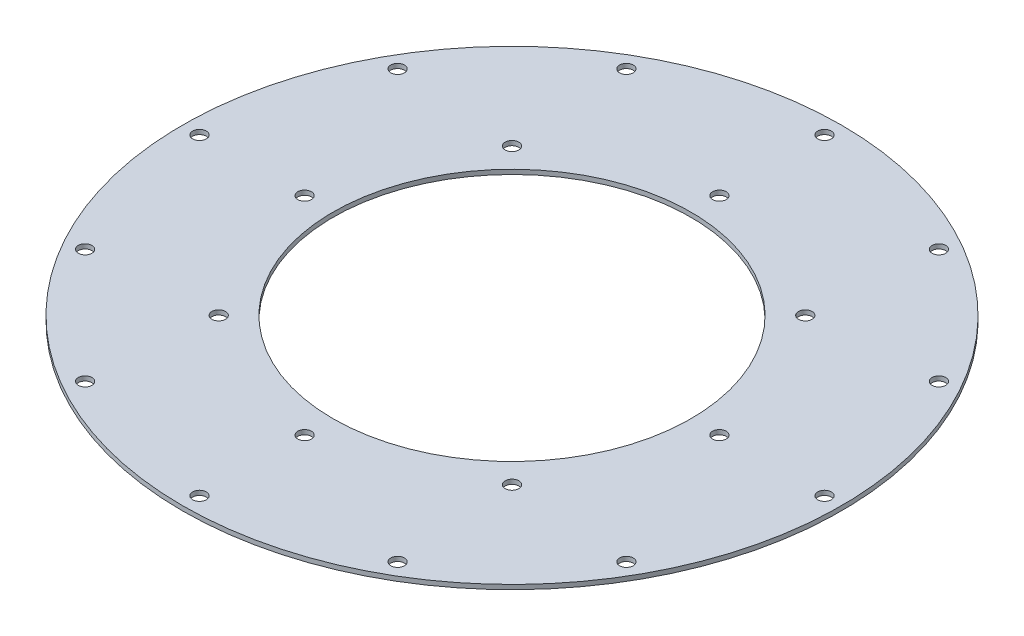
SolidWorks part; units mm, degrees
material "ASTM A36 Steel"
ref_plane "Front Plane" through (0, 0, 0) normal (0, 0, 1) x (1, 0, 0)
ref_plane "Top Plane" through (0, 0, 0) normal (0, 1, 0) x (1, 0, 0)
ref_plane "Right Plane" through (0, 0, 0) normal (1, 0, 0) x (0, 0, -1)
sketch "Sketch1" plane through (0, 0, 0) normal (0, 1, 0) x (1, 0, 0)
  circle A0 centre (0, 0) radius 290
  circle A1 centre (0, 0) radius 157.5
  dimension "D1" = 580
  dimension "D2" = 315
extrude "Boss-Extrude1" add sketch "Sketch1" along normal blind 4
sketch "Sketch2" plane through (0, 4, 0) normal (0, 1, 0) x (1, 0, 0)
  circle A1 centre (182.5, 0) radius 6
  dimension "D2" = 12
extrude "Cut-Extrude1" cut sketch "Sketch2" against normal blind 4
pattern_circular "CirPattern1" count 8 every 45 about axis through (0, 0, 0) along (0, 1, 0) of "Cut-Extrude1"
sketch "Sketch3" plane through (0, 4, 0) normal (0, 1, 0) x (1, 0, 0)
  circle A1 centre (275, 0) radius 6
  dimension "D2" = 12
extrude "Cut-Extrude2" cut sketch "Sketch3" against normal blind 4
pattern_circular "CirPattern2" count 12 every 30 about axis through (0, 0, 0) along (0, 1, 0) of "Cut-Extrude2"
